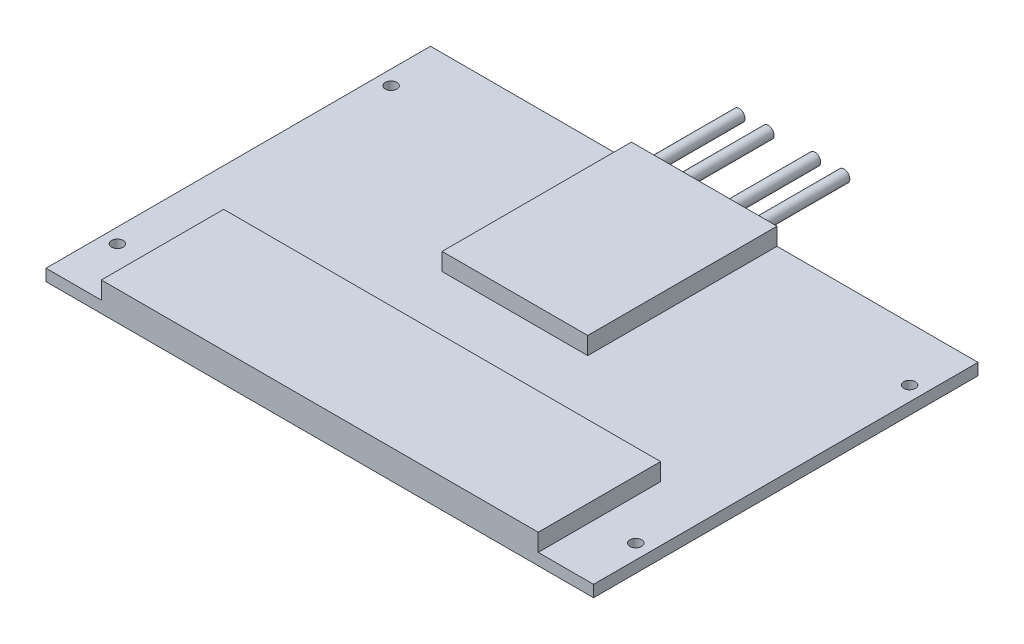
SolidWorks part; units mm, degrees
ref_plane "前视基准面" through (0, 0, 0) normal (0, 0, 1) x (1, 0, 0)
ref_plane "上视基准面" through (0, 0, 0) normal (0, 1, 0) x (1, 0, 0)
ref_plane "右视基准面" through (0, 0, 0) normal (1, 0, 0) x (0, 0, -1)
other "Configuration Table"
sketch "草图1" plane through (0, 0, 0) normal (0, 1, 0) x (1, 0, 0)
  line L1 (-94, 132) -> (94, 132)
  line L2 (-94, 132) -> (-94, 0)
  line L3 (-94, 0) -> (94, 0)
  line L4 (94, 132) -> (94, 0)
  point P4 (0, 0)
  dimension "D1" = 188
  dimension "D2" = 132
extrude "凸台-拉伸1" add sketch "草图1" along normal blind 4
sketch "草图2" plane through (0, 4, 0) normal (0, 1, 0) x (1, 0, 0)
  line L0 (94, 132) -> (-94, 132) construction
  line L1 (-25, 132) -> (25, 132)
  line L2 (-25, 132) -> (-25, 67)
  line L3 (-25, 67) -> (25, 67)
  line L4 (25, 132) -> (25, 67)
  line L5 (-94, 0) -> (94, 0) construction
  line L6 (-75, 0) -> (75, 0)
  line L7 (-75, 0) -> (-75, 42)
  line L8 (-75, 42) -> (75, 42)
  line L9 (75, 0) -> (75, 42)
  point P7 (0, 132)
  point P14 (0, 0)
  dimension "D1" = 50
  dimension "D2" = 65
  dimension "D3" = 42
  dimension "D4" = 150
extrude "凸台-拉伸2" add sketch "草图2" along normal blind 6
sketch "草图3" plane through (0, 0, -132) normal (0, 0, -1) x (-1, 0, 0)
  line L0 (0, 0) -> (0, 10) construction
  line L1 (-94, 0) -> (94, 0) construction
  line L2 (-25, 10) -> (25, 10) construction
  circle A0 centre (-18, 6.5) radius 2
  circle A1 centre (-8, 6.5) radius 2
  circle A2 centre (8, 6.5) radius 2
  circle A3 centre (18, 6.5) radius 2
  dimension "D2" = 4
  dimension "D3" = 6.5
  dimension "D4" = 8
  dimension "D5" = 10
  dimension "D1" = 10
extrude "凸台-拉伸3" add sketch "草图3" along normal blind 30
sketch "草图4" plane through (0, 4, 0) normal (0, 1, 0) x (1, 0, 0)
  line L0 (94, 0) -> (94, 132) construction
  line L1 (0, 0) -> (0, 132) construction
  line L2 (-75, 0) -> (75, 0) construction
  line L3 (25, 132) -> (-25, 132) construction
  line L4 (75, 0) -> (94, 0) construction
  circle A0 centre (89, 113.5) radius 2
  circle A1 centre (89, 19.5) radius 2
  circle A2 centre (-89, 19.5) radius 2
  circle A3 centre (-89, 113.5) radius 2
  point P18 (84.2933, 19.5)
  dimension "D1" = 4
  dimension "D2" = 94
  dimension "D3" = 5
  dimension "D4" = 19.5
extrude "切除-拉伸1" cut sketch "草图4" against normal blind 10
